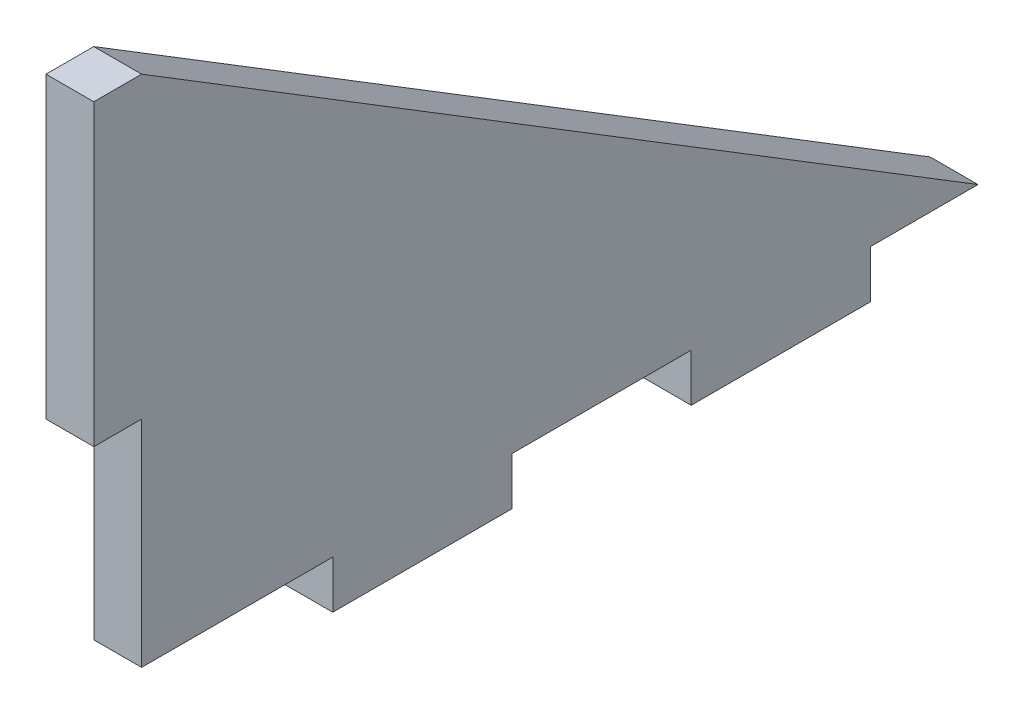
SolidWorks part; units mm, degrees
ref_plane "Front Plane" through (0, 0, 0) normal (0, 0, 1) x (1, 0, 0)
ref_plane "Top Plane" through (0, 0, 0) normal (0, 1, 0) x (1, 0, 0)
ref_plane "Right Plane" through (0, 0, 0) normal (1, 0, 0) x (0, 0, -1)
sketch "Sketch1" plane through (0, 0, 0) normal (1, 0, 0) x (0, 0, -1)
  line L0 (0, 0) -> (0, 43)
  line L1 (0, 43) -> (70, 0)
  line L2 (70, 0) -> (0, 0)
  line L4 (16, 0) -> (31, 0)
  line L5 (16, 0) -> (16, -4)
  line L6 (16, -4) -> (31, -4)
  line L7 (31, 0) -> (31, -4)
  line L8 (46, 0) -> (61, 0)
  line L9 (46, 0) -> (46, -4)
  line L10 (46, -4) -> (61, -4)
  line L11 (61, 0) -> (61, -4)
  line L12 (0, 43) -> (-4, 43)
  line L13 (0, 43) -> (0, 18)
  line L14 (0, 18) -> (-4, 18)
  line L15 (-4, 43) -> (-4, 18)
  point P12 (53.5, -4)
  point P13 (23.5, -4)
  dimension "D1" = 4
  dimension "D2" = 15
  dimension "D3" = 16
  dimension "D4" = 15
  dimension "D5" = 30
  dimension "D6" = 70
  dimension "D7" = 4
  dimension "D8" = 25
  dimension "D9" = 43
extrude "Boss-Extrude1" add sketch "Sketch1" along normal blind 4 contours L2 L1 L0 | L11 L2 L9 L10 | L7 L2 L5 L6 | L12 L15 L14 L0
